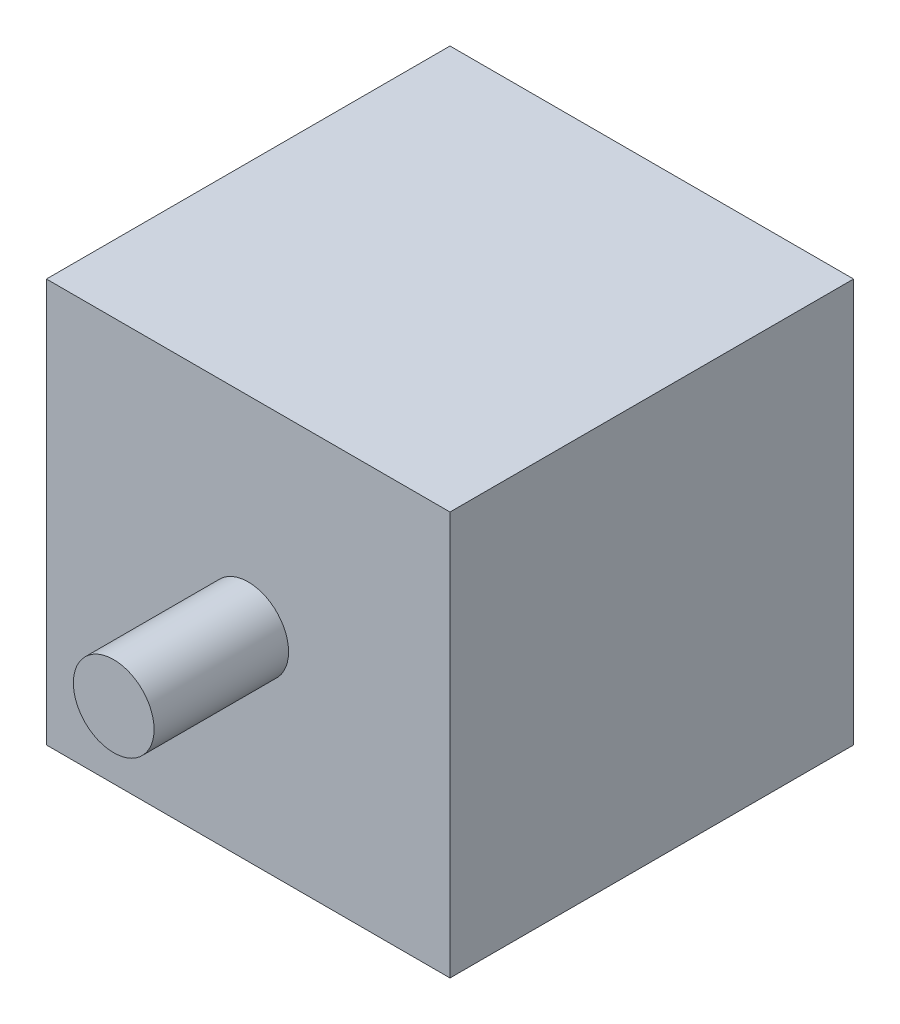
SolidWorks part; units mm, degrees
ref_plane "前视基准面" through (0, 0, 0) normal (0, 0, 1) x (1, 0, 0)
ref_plane "上视基准面" through (0, 0, 0) normal (0, 1, 0) x (1, 0, 0)
ref_plane "右视基准面" through (0, 0, 0) normal (1, 0, 0) x (0, 0, -1)
sketch "草图2" plane through (0, 0, 0) normal (0, 0, 1) x (1, 0, 0)
  line L1 (-7.5, 7.5) -> (7.5, 7.5)
  line L2 (-7.5, 7.5) -> (-7.5, -7.5)
  line L3 (-7.5, -7.5) -> (7.5, -7.5)
  line L4 (7.5, 7.5) -> (7.5, -7.5)
  line L5 (-7.5, 7.5) -> (7.5, -7.5) construction
  line L6 (-7.5, -7.5) -> (7.5, 7.5) construction
  point P0 (0, 0)
  dimension "D1" = 15
  dimension "D2" = 15
extrude "凸台-拉伸1" add sketch "草图2" along normal blind 15
sketch "草图3" plane through (0, 0, 15) normal (0, 0, 1) x (1, 0, 0)
  circle A0 centre (0, 0) radius 1.5
extrude "凸台-拉伸2" add sketch "草图3" along normal blind 5
